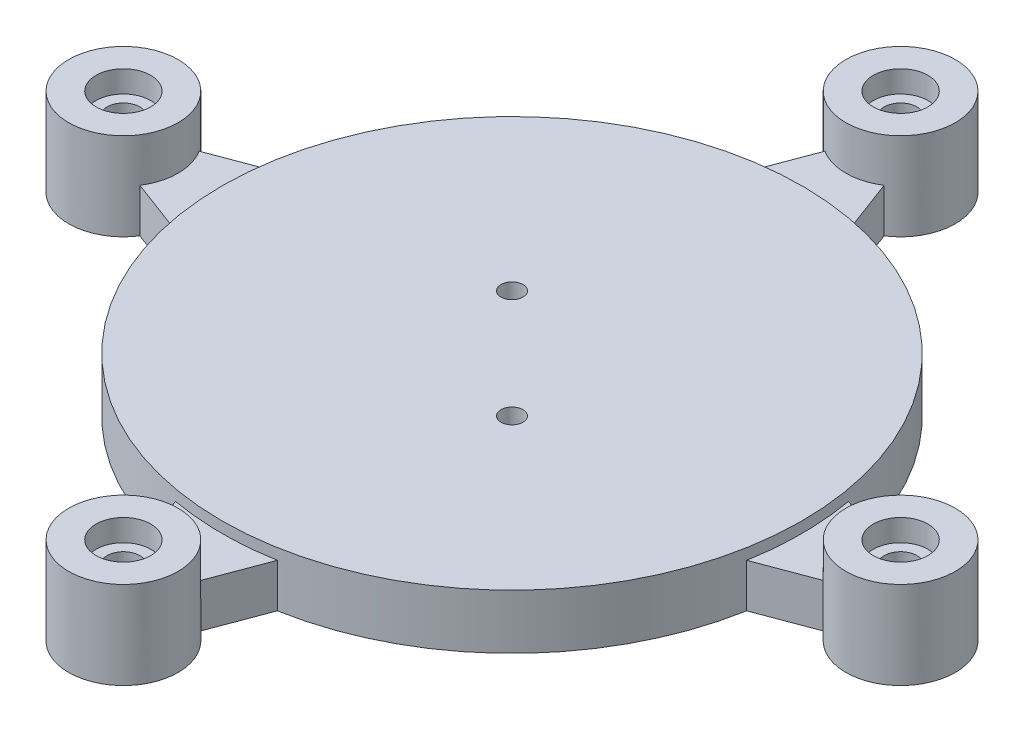
SolidWorks part; units mm, degrees
ref_plane "Alzado" through (0, 0, 0) normal (0, 0, 1) x (1, 0, 0)
ref_plane "Planta" through (0, 0, 0) normal (0, 1, 0) x (1, 0, 0)
ref_plane "Vista lateral" through (0, 0, 0) normal (1, 0, 0) x (0, 0, -1)
sketch "Croquis1" plane through (0, 0, 0) normal (0, 1, 0) x (1, 0, 0)
  circle A0 centre (0, 0) radius 26.5
  dimension "D1" = 53
extrude "Saliente-Extruir1" add sketch "Croquis1" along normal blind 5
sketch "Croquis2" plane through (0, 0, 0) normal (0, 1, 0) x (1, 0, 0)
  line L0 (0, 26.5) -> (0, 30.5) construction
  line L1 (-3, 30.5) -> (3, 30.5) construction
  line L2 (-4.5, 26.5) -> (4.5, 26.5) construction
  line L3 (-5.0291, 25.089) -> (-2.7025, 31.2933)
  line L4 (5.0291, 25.089) -> (2.7025, 31.2933)
  line L5 (0, 30.5) -> (0, 35.5) construction
  line L6 (0, 26.5) -> (0, 25.089) construction
  line L7 (-5.0291, 25.089) -> (5.0291, 25.089)
  circle A0 centre (0, 0) radius 26.5 construction
  arc A1 (2.7025, 31.2933) -> (-2.7025, 31.2933) centre (0, 35.5) ccw
  dimension "D1" = 4
  dimension "D2" = 6
  dimension "D3" = 9
  dimension "D4" = 5
extrude "Saliente-Extruir2" add sketch "Croquis2" along normal blind 4
sketch "Croquis3" plane through (0, 4, 0) normal (0, 1, 0) x (1, 0, 0)
  circle A0 centre (0, 35.5) radius 5
extrude "Saliente-Extruir3" add sketch "Croquis3" along normal blind 4
sketch "Croquis4" plane through (0, 8, 0) normal (0, 1, 0) x (1, 0, 0)
  circle A0 centre (0, 35.5) radius 2.5
  dimension "D1" = 5
extrude "Cortar-Extruir1" cut sketch "Croquis4" against normal blind 2
sketch "Croquis5" plane through (0, 6, 0) normal (0, 1, 0) x (1, 0, 0)
  circle A0 centre (0, 35.5) radius 1.5
  dimension "D1" = 3
extrude "Cortar-Extruir2" cut sketch "Croquis5" against normal through all
pattern_circular "MatrizC1" count 4 every 90 about axis through (0, 0, 0) along (0, 1, 0) of "Saliente-Extruir2", "Saliente-Extruir3", "Cortar-Extruir1", "Cortar-Extruir2"
sketch "Croquis6" plane through (0, 5, 0) normal (0, 1, 0) x (1, 0, 0)
  line L0 (0, -26.5) -> (0, 26.5) construction
  line L1 (-18.7383, 18.7383) -> (18.7383, -18.7383) construction
  line L2 (0, 0) -> (7.7696, 7.7696) construction
  line L3 (4.9497, -4.9497) -> (12.7193, 2.8198)
  line L4 (-4.9497, 4.9497) -> (2.8198, 12.7193)
  arc A0 (-4.6545, -26.088) -> (4.6545, -26.088) centre (0, 0) ccw construction
  circle A1 centre (0, 0) radius 26.5 construction
  circle A2 centre (-4.9497, 4.9497) radius 1
  circle A3 centre (4.9497, -4.9497) radius 1
  point P12 (0, 0)
  dimension "D4" = 2
  dimension "D2" = 7
  dimension "D3" = 7
  dimension "D1" = 2
extrude "Cortar-Extruir3" cut sketch "Croquis6" against normal through all
